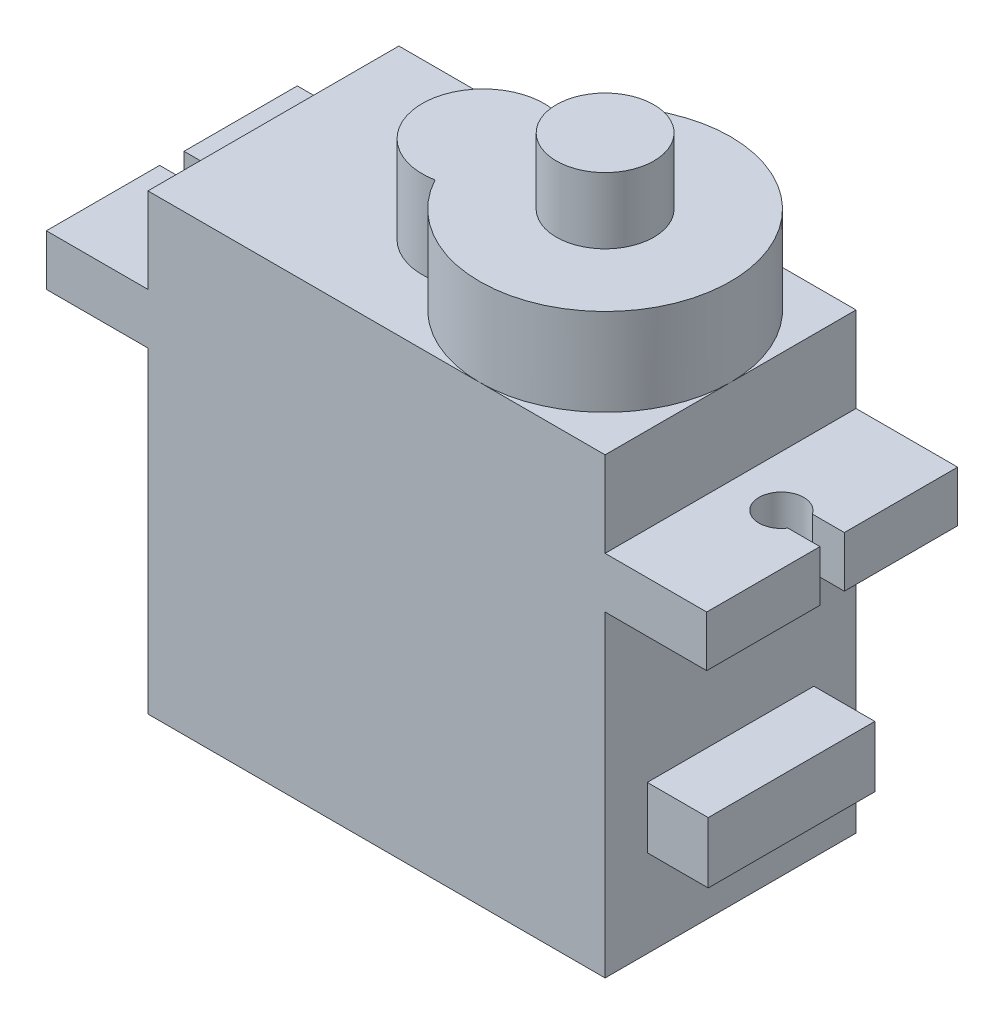
SolidWorks part; units mm, degrees
material "ABS"
ref_plane "Front Plane" through (0, 0, 0) normal (0, 0, 1) x (1, 0, 0)
ref_plane "Top Plane" through (0, 0, 0) normal (0, 1, 0) x (1, 0, 0)
ref_plane "Right Plane" through (0, 0, 0) normal (1, 0, 0) x (0, 0, -1)
sketch "Sketch1" plane through (0, 0, 0) normal (0, 0, 1) x (1, 0, 0)
  line L0 (0, 0) -> (22.5, 0)
  line L1 (22.5, 0) -> (22.5, 15.6)
  line L2 (22.5, 18.1) -> (27.5, 18.1)
  line L3 (27.5, 18.1) -> (27.5, 15.6)
  line L4 (27.5, 15.6) -> (22.5, 15.6)
  line L5 (22.5, 18.1) -> (22.5, 22.3)
  line L6 (22.5, 22.3) -> (0, 22.3)
  line L7 (0, 22.3) -> (0, 18.1)
  line L8 (0, 18.1) -> (-5, 18.1)
  line L9 (-5, 18.1) -> (-5, 15.6)
  line L10 (-5, 15.6) -> (0, 15.6)
  line L11 (0, 15.6) -> (0, 0)
  dimension "D1" = 22.3
  dimension "D2" = 15.6
  dimension "D3" = 2.5
  dimension "D4" = 5
  dimension "D5" = 5
  dimension "D6" = 2.5
  dimension "D7" = 15.6
  dimension "D8" = 22.5
  dimension "D9" = 22.5
extrude "Boss-Extrude1" add sketch "Sketch1" along normal blind 12.35
sketch "Sketch2" plane through (0, 22.3, 0) normal (0, 1, 0) x (1, 0, 0)
  line L0 (22.5, -12.35) -> (22.5, 0) construction
  line L1 (22.5, 0) -> (0, 0) construction
  line L2 (22.5, -12.35) -> (0, -12.35) construction
  line L3 (0, -6.175) -> (22.5, -6.175) construction
  line L4 (0, -12.35) -> (0, 0) construction
  arc A0 (10.8974, -9.1199) -> (10.8974, -3.2301) centre (16.325, -6.175) ccw
  arc A1 (10.8974, -3.2301) -> (10.8974, -9.1199) centre (10.325, -6.175) ccw
  dimension "D2" = 6
  dimension "D1" = 6
extrude "Boss-Extrude2" add sketch "Sketch2" along normal blind 4.3
sketch "Sketch3" plane through (0, 26.6, 0) normal (0, 1, 0) x (1, 0, 0)
  circle A0 centre (16.325, -6.175) radius 2.4
  dimension "D1" = 4.8
extrude "Boss-Extrude3" add sketch "Sketch3" along normal blind 3.25
sketch "Sketch4" plane through (22.5, 0, 0) normal (1, 0, 0) x (0, 0, -1)
  line L0 (-12.35, 0) -> (0, 0) construction
  line L1 (-10.275, 7.3) -> (-2.075, 7.3)
  line L2 (-10.275, 7.3) -> (-10.275, 4.3)
  line L3 (-10.275, 4.3) -> (-2.075, 4.3)
  line L4 (-2.075, 7.3) -> (-2.075, 4.3)
  line L5 (-6.175, 15.6) -> (-6.175, 0) construction
  line L6 (-12.35, 15.6) -> (0, 15.6) construction
  line L7 (-6.175, 7.3) -> (-6.175, 4.3) construction
  dimension "D1" = 4.3
  dimension "D2" = 8.2
  dimension "D3" = 3
extrude "Boss-Extrude4" add sketch "Sketch4" along normal blind 3
sketch "Sketch5" plane through (0, 18.1, 0) normal (0, 1, 0) x (1, 0, 0)
  line L0 (27.5, -12.35) -> (22.5, -12.35) construction
  line L1 (27.5, -12.35) -> (27.5, 0) construction
  line L2 (-5, -12.35) -> (-5, 0) construction
  line L3 (0, -12.35) -> (-5, -12.35) construction
  line L4 (-3.6, -6.175) -> (-5, -6.175) construction
  line L5 (-3.422, -5.575) -> (-5, -5.575)
  line L6 (-3.422, -6.775) -> (-5, -6.775)
  line L7 (-5, -5.575) -> (-5, -6.775)
  line L8 (25, -6.175) -> (27.5, -6.175) construction
  line L9 (25.922, -6.775) -> (27.5, -6.775)
  line L10 (27.5, -5.575) -> (25.922, -5.575)
  line L11 (27.5, -5.575) -> (27.5, -6.775)
  arc A0 (25.922, -5.575) -> (25.922, -6.775) centre (25, -6.175) ccw
  arc A1 (-3.422, -6.775) -> (-3.422, -5.575) centre (-2.5, -6.175) ccw
  dimension "D1" = 2.2
  dimension "D4" = 2.2
  dimension "D2" = 6.175
  dimension "D3" = 2.5
  dimension "D5" = 2.5
  dimension "D6" = 6.175
  dimension "D7" = 0.6
  dimension "D8" = 0.6
  dimension "D9" = 0.6
  dimension "D10" = 0.6
extrude "Cut-Extrude1" cut sketch "Sketch5" against normal blind 3
